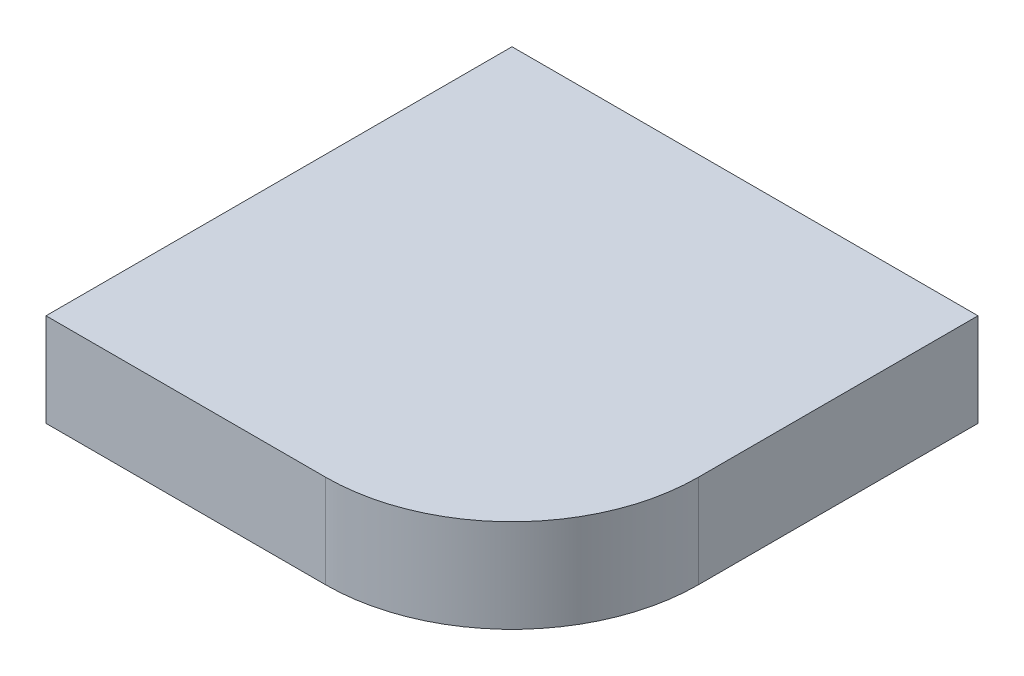
SolidWorks part; units mm, degrees
ref_plane "Front Plane" through (0, 0, 0) normal (0, 0, 1) x (1, 0, 0)
ref_plane "Top Plane" through (0, 0, 0) normal (0, 1, 0) x (1, 0, 0)
ref_plane "Right Plane" through (0, 0, 0) normal (1, 0, 0) x (0, 0, -1)
sketch "Sketch1" plane through (0, 0, 0) normal (0, 1, 0) x (1, 0, 0)
  line L0 (0, -20) -> (-30, -20)
  line L1 (-30, -20) -> (-30, 30)
  line L2 (-30, 30) -> (20, 30)
  line L3 (20, 30) -> (20, 0)
  arc A0 (0, -20) -> (20, 0) centre (0, 0) ccw
  dimension "D1" = 20
  dimension "D2" = 30
  dimension "D3" = 30
extrude "Boss-Extrude1" add sketch "Sketch1" along normal blind 10
